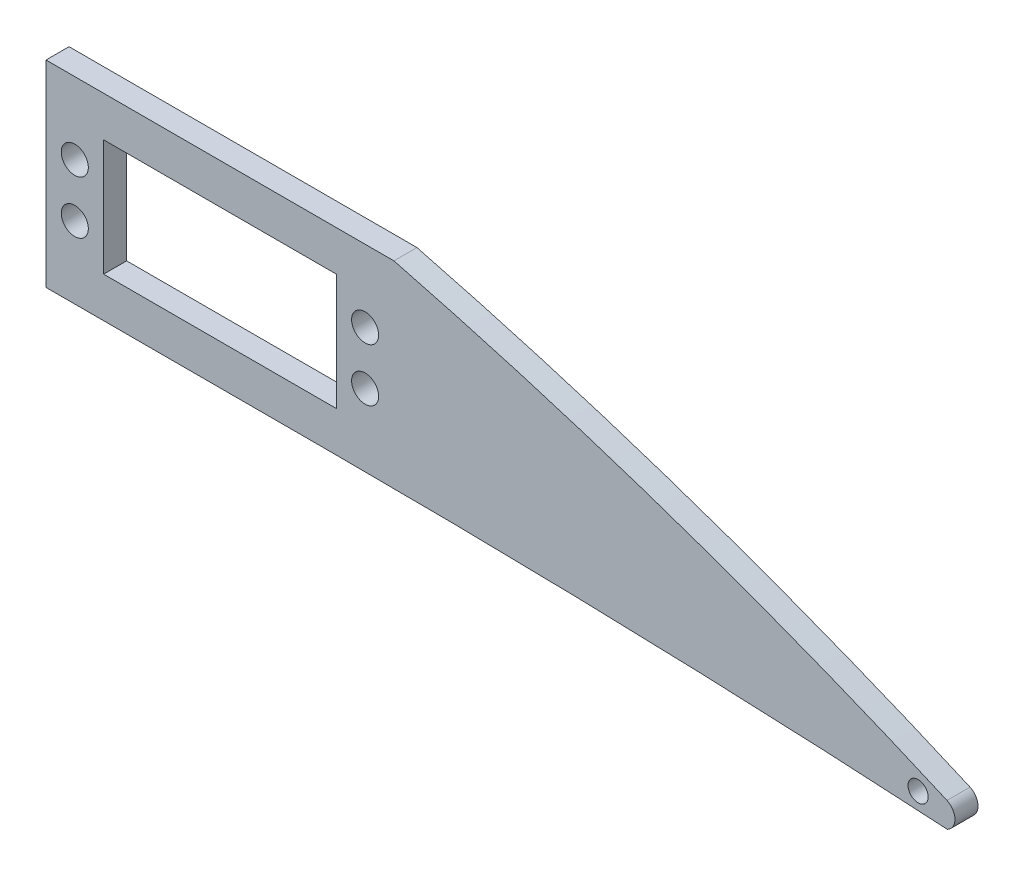
SolidWorks part; units mm, degrees
ref_plane "Płaszczyzna przednia" through (0, 0, 0) normal (0, 0, 1) x (1, 0, 0)
ref_plane "Płaszczyzna górna" through (0, 0, 0) normal (0, 1, 0) x (1, 0, 0)
ref_plane "Płaszczyzna prawa" through (0, 0, 0) normal (1, 0, 0) x (0, 0, -1)
sketch "Szkic2" plane through (0, 0, 0) normal (0, 0, 1) x (1, 0, 0)
  line L10 (-91.9323, 0) -> (51.5424, 0) construction
  line L11 (0, 24.6927) -> (0, -16.8499) construction
  line L13 (-20.2, 10.1) -> (20.2, 10.1)
  line L14 (-20.2, 10.1) -> (-20.2, -10.1)
  line L15 (-20.2, -10.1) -> (20.2, -10.1)
  line L16 (20.2, 10.1) -> (20.2, -10.1)
  line L17 (-30.2, 17.1) -> (30.2, 17.1)
  line L18 (-30.2, 17.1) -> (-30.2, -17.1)
  line L19 (-30.2, -17.1) -> (19.1974, -17.1)
  circle A4 centre (-25.2, 4.6) radius 2.35
  circle A5 centre (25.2, 4.6) radius 2.35
  circle A6 centre (25.2, -4.6) radius 2.35
  circle A7 centre (-25.2, -4.6) radius 2.35
  arc A8 (30.2, 17.1) -> (126.2167, -16.0095) centre (-123.1666, -583.436) cw
  arc A9 (19.1974, -17.1) -> (126.2693, -20.3334) centre (19.1974, -1791.5029) cw
  arc A10 (126.2167, -16.0095) -> (126.2693, -20.3334) centre (125.2, -18.1842) cw
  circle A11 centre (121.2, -17.1334) radius 1.75
  point P30 (0, -10.1)
  point P31 (20.2, 0)
  dimension "D16" = 4.7
  dimension "D3" = 3.5
  dimension "D2" = 105
  dimension "D4" = 4
  dimension "D5" = 3.2
  dimension "D10" = 40.4
  dimension "D11" = 20.2
  dimension "D12" = 7
  dimension "D13" = 7
  dimension "D15" = 10
  dimension "D17" = 5
  dimension "D18" = 5.5
extrude "Dodanie-wyciągnięcie1" add sketch "Szkic2" along normal blind 4
